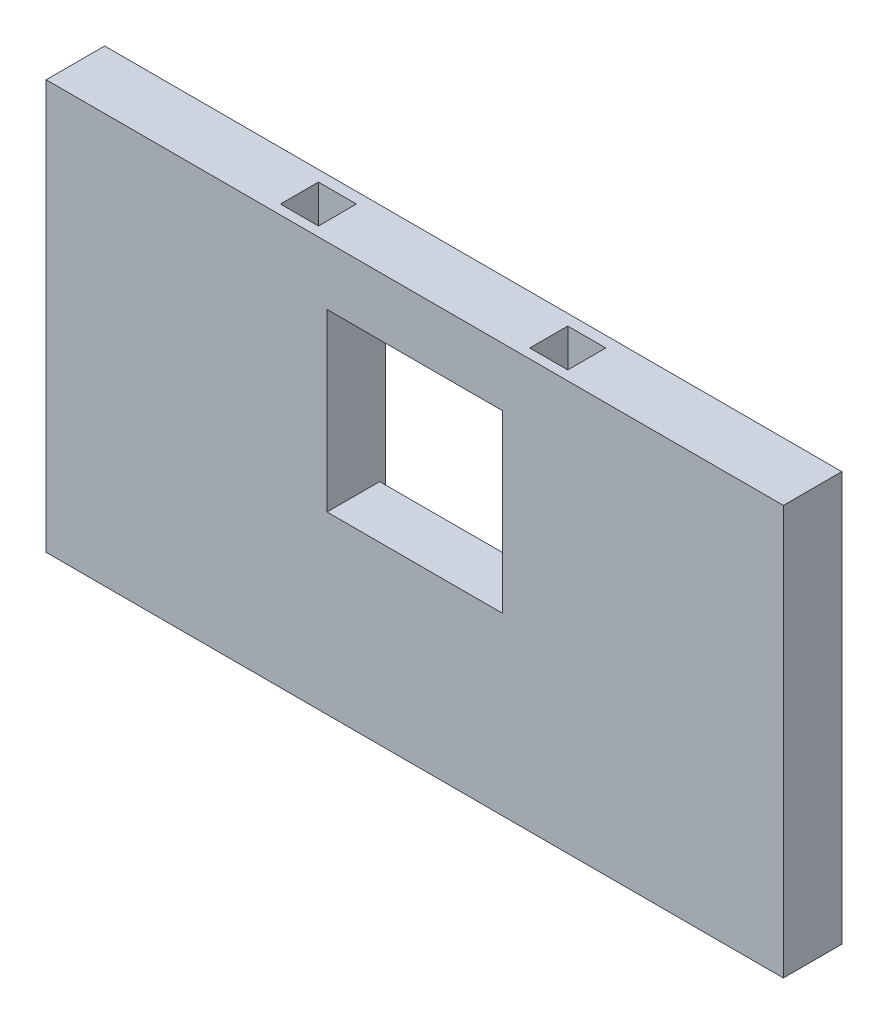
SolidWorks part; units mm, degrees
ref_plane "Front Plane" through (0, 0, 0) normal (0, 0, 1) x (1, 0, 0)
ref_plane "Top Plane" through (0, 0, 0) normal (0, 1, 0) x (1, 0, 0)
ref_plane "Right Plane" through (0, 0, 0) normal (1, 0, 0) x (0, 0, -1)
sketch "Sketch1" plane through (0, 0, 0) normal (0, 0, 1) x (1, 0, 0)
  line L1 (-107.8214, 92.0904) -> (-7.8214, 92.0904)
  line L3 (-107.8214, 44.0904) -> (-7.8214, 44.0904)
  line L5 (-107.8214, 92.0904) -> (-182.8214, 92.0904)
  line L7 (-107.8214, 44.0904) -> (-182.8214, 44.0904)
  line L8 (-182.8214, 92.0904) -> (-182.8214, 44.0904)
  line L9 (-7.8214, 92.0904) -> (117.1786, 92.0904)
  line L11 (-7.8214, 44.0904) -> (117.1786, 44.0904)
  line L12 (117.1786, 92.0904) -> (117.1786, 44.0904)
  dimension "D1" = 48
  dimension "D2" = 100
  dimension "D3" = 75
  dimension "D4" = 125
extrude "Boss-Extrude1" add sketch "Sketch1" along normal blind 20
sketch "Sketch5" plane through (0, 92.0904, 0) normal (0, 1, 0) x (1, 0, 0)
  line L0 (-182.8214, -20) -> (-157.8214, -20) construction
  line L2 (117.1786, -20) -> (-182.8214, -20) construction
  line L3 (-157.8214, -20) -> (-57.8214, -20) construction
  line L4 (-57.8214, -20) -> (-66.3214, -20) construction
  line L5 (-66.3214, -20) -> (-66.3214, -16) construction
  line L6 (-66.3214, -16) -> (-66.3214, -10) construction
  line L7 (-66.3214, -10) -> (-47.3214, -10) construction
  circle A0 centre (-66.3214, -10) radius 5.25
  circle A1 centre (-47.3214, -10) radius 5.25
extrude "Cut-Extrude4" cut sketch "Sketch5" against normal blind 20
sketch "Sketch6" plane through (0, 92.0904, 0) normal (0, 1, 0) x (1, 0, 0)
  line L0 (-182.8214, 0) -> (-105.6914, 0) construction
  line L1 (117.1786, 0) -> (-182.8214, 0) construction
  line L2 (-105.6914, 0) -> (-105.6914, -4) construction
  line L3 (-105.9414, -3.75) -> (-92.9414, -3.75)
  line L8 (-92.9414, -3.75) -> (-92.9414, -16.75)
  line L9 (-105.9414, -16.75) -> (-92.9414, -16.75)
  line L10 (-105.9414, -3.75) -> (-105.9414, -16.75)
extrude "Cut-Extrude5" cut sketch "Sketch6" against normal blind 15.5
sketch "Sketch7" plane through (0, 92.0904, 0) normal (0, 1, 0) x (1, 0, 0)
  line L0 (117.1786, 0) -> (-7.9138, 0) construction
  line L1 (117.1786, 0) -> (-182.8214, 0) construction
  line L2 (-7.9138, 0) -> (-7.9138, -4) construction
  line L3 (-7.6638, -3.75) -> (-20.6638, -3.75)
  line L8 (-20.6638, -3.75) -> (-20.6638, -16.75)
  line L9 (-7.6638, -16.75) -> (-20.6638, -16.75)
  line L10 (-7.6638, -3.75) -> (-7.6638, -16.75)
extrude "Cut-Extrude6" cut sketch "Sketch7" against normal blind 15.5
sketch "Sketch8" plane through (0, 0, 20) normal (0, 0, 1) x (1, 0, 0)
  line L0 (117.1786, 44.0904) -> (117.1786, 92.0904) construction
  line L1 (-182.8214, 44.0904) -> (117.1786, 44.0904)
  line L2 (-182.8214, 44.0904) -> (-182.8214, -57.9096)
  line L3 (-182.8214, -57.9096) -> (117.1786, -57.9096)
  line L4 (117.1786, 44.0904) -> (117.1786, -57.9096)
  dimension "D1" = 150
extrude "Boss-Extrude2" add sketch "Sketch8" against normal up to surface (20 mm away) up to face at (-32.8214, 68.0904, 0)
sketch "Sketch9" plane through (0, 92.0904, 0) normal (0, 1, 0) x (1, 0, 0)
  line L1 (-105.9414, -3.75) -> (-105.9414, -16.75) construction
  line L2 (-7.6638, -3.75) -> (-7.6638, -16.75) construction
  line L4 (117.1786, 0) -> (-182.8214, 0) construction
  line L5 (69.3362, 0) -> (69.3362, -20) construction
  line L6 (117.1786, -20) -> (-182.8214, -20) construction
  line L8 (117.1786, -20) -> (69.3362, -20)
  line L9 (117.1786, -20) -> (117.1786, 0)
  line L10 (117.1786, 0) -> (69.3362, 0)
  line L11 (69.3362, -20) -> (69.3362, 0)
  dimension "D1" = 77
extrude "Cut-Extrude7" cut sketch "Sketch9" against normal up to vertex
sketch "Sketch11" plane through (0, 0, 20) normal (0, 0, 1) x (1, 0, 0)
  line L0 (69.3362, 92.0904) -> (-182.8214, 92.0904) construction
  line L1 (-56.7426, 92.0904) -> (-56.7426, 62.0904) construction
  line L3 (-26.7426, 62.0904) -> (-26.7426, 12.0904)
  line L4 (-26.7426, 12.0904) -> (-86.7426, 12.0904)
  line L5 (-86.7426, 12.0904) -> (-86.7426, 62.0904)
  line L8 (-26.7426, 62.0904) -> (-26.7426, 64.0904)
  line L9 (-26.7426, 64.0904) -> (-86.7426, 64.0904)
  line L10 (-86.7426, 62.0904) -> (-86.7426, 64.0904)
  point P5 (69.3362, 92.0904)
  point P10 (-56.7426, 62.0904)
  point P12 (-56.7426, 62.0904)
  dimension "D1" = 30
  dimension "D2" = 60
  dimension "D4" = 2
extrude "Cut-Extrude9" cut sketch "Sketch11" against normal blind 40
ref_plane "Plane1" through (-86.7426, 0, 0) normal (1, 0, 0) x (0, 0, -1)
sketch "Sketch14" plane through (-86.7426, 0, 0) normal (1, 0, 0) x (0, 0, -1)
  line L0 (0, 64.0904) -> (-20, 67.0904)
  line L3 (-20, -57.9096) -> (-20, 92.0904) construction
  line L4 (-20, 67.0904) -> (-20, 64.0904)
  line L9 (0, 64.0904) -> (-20, 64.0904)
extrude "Cut-Extrude10" cut sketch "Sketch14" along normal up to surface (60 mm away) up to face at (-26.7426, 38.0904, 10)
sketch "Sketch17" plane through (0, 0, 0) normal (0, 0, -1) x (-1, 0, 0)
  line L0 (-69.3362, 92.0904) -> (182.8214, 92.0904) construction
  line L1 (86.7426, 92.0904) -> (26.7426, 92.0904)
  line L2 (86.7426, 92.0904) -> (86.7426, 87.0904)
  line L3 (86.7426, 87.0904) -> (26.7426, 87.0904)
  line L4 (26.7426, 92.0904) -> (26.7426, 87.0904)
  line L5 (86.7426, 64.0904) -> (86.7426, 12.0904) construction
  line L6 (26.7426, 12.0904) -> (26.7426, 64.0904) construction
  dimension "D1" = 0
  dimension "D2" = 0
  dimension "D3" = 5
extrude "Cut-Extrude12" cut sketch "Sketch17" against normal blind 38
ref_plane "Plane2" through (-26.7426, 0, 0) normal (-1, 0, 0) x (0, 0, 1)
sketch "Sketch19" plane through (-26.7426, 0, 0) normal (-1, 0, 0) x (0, 0, 1)
  line L0 (0, 12.0904) -> (2, 12.0904)
  line L1 (0, 12.0904) -> (20, 12.0904) construction
  line L2 (0, -57.9096) -> (0, 92.0904) construction
  line L3 (2, 12.0904) -> (8, -57.9096)
  line L4 (0, -57.9096) -> (20, -57.9096) construction
  line L5 (8, -57.9096) -> (0, -57.9096)
  line L6 (0, -57.9096) -> (0, 12.0904)
  dimension "D1" = 8
extrude "Cut-Extrude13" cut sketch "Sketch19" along normal up to surface (60 mm away) up to face at (-86.7426, 38.8404, 10)
sketch "Sketch15" plane through (0, 92.0904, 0) normal (0, 1, 0) x (1, 0, 0)
  line L0 (-66.3214, -10) -> (-47.3214, -10) construction
  line L1 (69.3362, 0) -> (-26.7426, 0) construction
  line L2 (-76.8214, -20) -> (-36.8214, -20)
  line L3 (-76.8214, -20) -> (-76.8214, 0)
  line L4 (-76.8214, 0) -> (-36.8214, 0)
  line L5 (-36.8214, -20) -> (-36.8214, 0)
  line L6 (-76.8214, -20) -> (-36.8214, 0) construction
  line L7 (-76.8214, 0) -> (-36.8214, -20) construction
  circle A0 centre (-66.3214, -10) radius 5.25 construction
  circle A1 centre (-47.3214, -10) radius 5.25 construction
  circle A2 centre (-66.3214, -10) radius 5.25
  circle A3 centre (-47.3214, -10) radius 5.25
  point P7 (-56.8214, -10)
  dimension "D1" = 40
extrude "Cut-Extrude11" [suppressed] cut sketch "Sketch15" against normal blind 5
sketch "Sketch10" plane through (0, 0, 0) normal (0, 0, -1) x (-1, 0, 0)
  line L3 (-69.3362, -7.9096) -> (182.8214, -7.9096)
  line L6 (182.8214, 92.0904) -> (182.8214, -57.9096) construction
  line L8 (-69.3362, -57.9096) -> (182.8214, -57.9096)
  line L9 (-69.3362, -57.9096) -> (-69.3362, -7.9096)
  line L11 (182.8214, -57.9096) -> (182.8214, -7.9096)
  dimension "D1" = 50
extrude "Cut-Extrude8" cut sketch "Sketch10" against normal blind 310
sketch "Sketch20" plane through (0, -7.9096, 0) normal (0, -1, 0) x (1, 0, 0)
  line L8 (69.3362, 20) -> (-182.8214, 20)
  line L9 (-182.8214, 20) -> (-182.8214, 0)
  line L10 (-182.8214, 0) -> (-86.7426, 0)
  line L11 (-86.7426, 0) -> (-86.7426, 3.7143)
  line L12 (-86.7426, 3.7143) -> (-26.7426, 3.7143)
  line L13 (-26.7426, 3.7143) -> (-26.7426, 0)
  line L14 (-26.7426, 0) -> (69.3362, 0)
  line L15 (69.3362, 0) -> (69.3362, 20)
  line L16 (69.3362, 20) -> (-182.8214, 20)
  line L17 (-182.8214, 20) -> (-182.8214, 0)
  line L18 (-182.8214, 0) -> (-86.7426, 0)
  line L19 (-86.7426, 0) -> (-86.7426, 3.7143)
  line L20 (-86.7426, 3.7143) -> (-26.7426, 3.7143)
  line L21 (-26.7426, 3.7143) -> (-26.7426, 0)
  line L22 (-26.7426, 0) -> (69.3362, 0)
  line L23 (69.3362, 0) -> (69.3362, 20)
  dimension "D1" = 0
extrude "Boss-Extrude3" add sketch "Sketch20" along normal blind 50
sketch "Sketch21" plane through (0, 0, 20) normal (0, 0, 1) x (1, 0, 0)
  line L0 (-182.8214, 92.0904) -> (-182.8214, -57.9096) construction
  line L1 (69.3362, -57.9096) -> (-182.8214, -57.9096)
  line L2 (69.3362, -57.9096) -> (69.3362, -47.9096)
  line L3 (69.3362, -47.9096) -> (-182.8214, -47.9096)
  line L4 (-182.8214, -57.9096) -> (-182.8214, -47.9096)
  dimension "D1" = 10
extrude "Cut-Extrude14" cut sketch "Sketch21" against normal blind 54
sketch "Sketch23" plane through (0, 0, 20) normal (0, 0, 1) x (1, 0, 0)
  line L1 (-26.7426, 92.0904) -> (-86.7426, 92.0904)
  line L2 (-26.7426, 92.0904) -> (-26.7426, 87.0904)
  line L3 (-26.7426, 87.0904) -> (-86.7426, 87.0904)
  line L4 (-86.7426, 92.0904) -> (-86.7426, 87.0904)
extrude "Boss-Extrude5" add sketch "Sketch23" against normal up to surface (20 mm away) up to face at (-56.7426, 39.9237, 0)
sketch "Sketch24" plane through (0, 0, 20) normal (0, 0, 1) x (1, 0, 0)
  line L0 (-26.7426, 11) -> (-26.7426, -11) construction
  line L2 (-86.7426, 67.0904) -> (-86.7426, 72.0904)
  line L3 (-86.7426, 72.0904) -> (-26.7426, 72.0904)
  line L4 (-26.7426, 67.0904) -> (-26.7426, 72.0904)
  line L7 (-86.7426, 67.0904) -> (-86.7426, 61.0107)
  line L8 (-86.7426, 61.0107) -> (-26.7426, 61.0107)
  line L9 (-26.7426, 67.0904) -> (-26.7426, 61.0107)
  dimension "D1" = 5
extrude "Cut-Extrude15" cut sketch "Sketch24" against normal up to surface (20 mm away) up to face at (-56.7426, 15.0904, 0)
sketch "Sketch22" plane through (0, 0, 20) normal (0, 0, 1) x (1, 0, 0)
  line L1 (-26.7426, 92.0904) -> (-86.7426, 92.0904)
  line L2 (-26.7426, 92.0904) -> (-26.7426, 87.0904)
  line L3 (-26.7426, 87.0904) -> (-86.7426, 87.0904)
  line L4 (-86.7426, 92.0904) -> (-86.7426, 87.0904)
extrude "Boss-Extrude4" add sketch "Sketch22" against normal up to surface (20 mm away)
